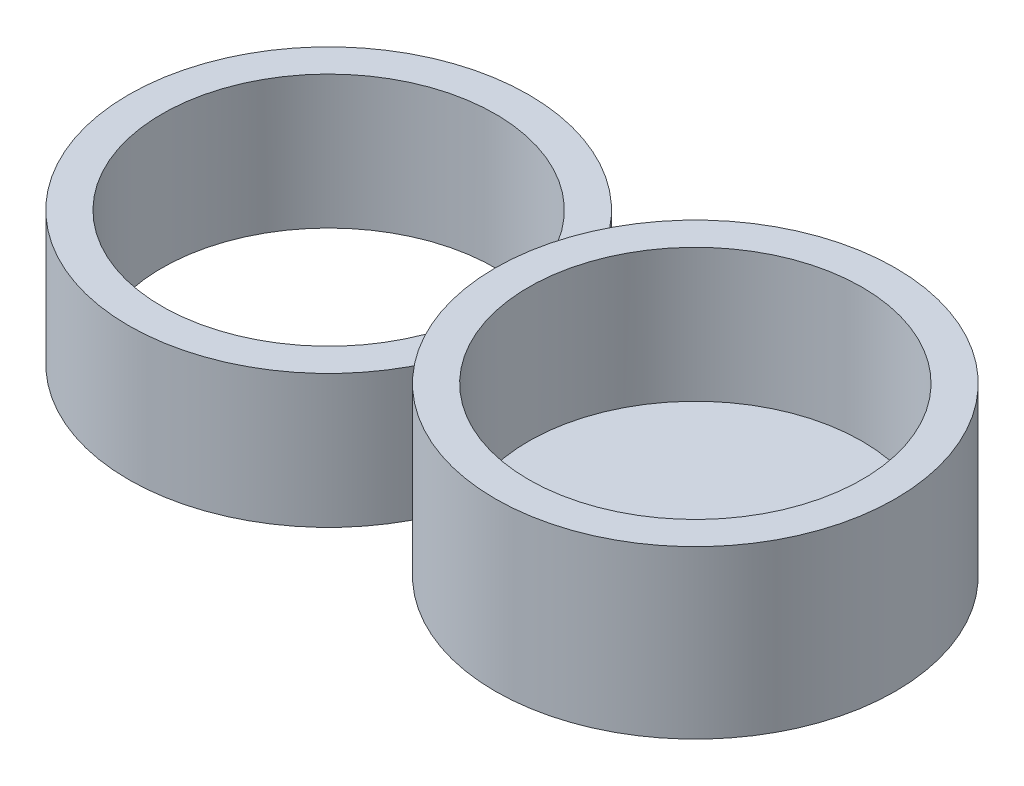
SolidWorks part; units mm, degrees
ref_plane "Спереди" through (0, 0, 0) normal (0, 0, 1) x (1, 0, 0)
ref_plane "Сверху" through (0, 0, 0) normal (0, 1, 0) x (1, 0, 0)
ref_plane "Справа" through (0, 0, 0) normal (1, 0, 0) x (0, 0, -1)
sketch "Эскиз1" plane through (0, 0, 0) normal (0, 1, 0) x (1, 0, 0)
  arc A0 (-5.5, -2.3979) -> (-5.5, 2.3979) centre (0, 0) ccw
  circle A1 centre (0, 0) radius 5
  circle A2 centre (-11, 0) radius 5
  arc A3 (-5.5, 2.3979) -> (-5.5, -2.3979) centre (-11, 0) ccw
extrude "Бобышка-Вытянуть1" add sketch "Эскиз1" along normal blind 4
sketch "Эскиз2" plane through (0, 0, 0) normal (0, -1, 0) x (1, 0, 0)
  circle A0 centre (0, 0) radius 6
extrude "Бобышка-Вытянуть2" add sketch "Эскиз2" against normal blind 1
sketch "Эскиз4" plane through (0, 4, 0) normal (0, 1, 0) x (1, 0, 0)
  circle A0 centre (0, 0) radius 6
  circle A1 centre (0, 0) radius 5
extrude "Бобышка-Вытянуть3" add sketch "Эскиз4" along normal blind 1
